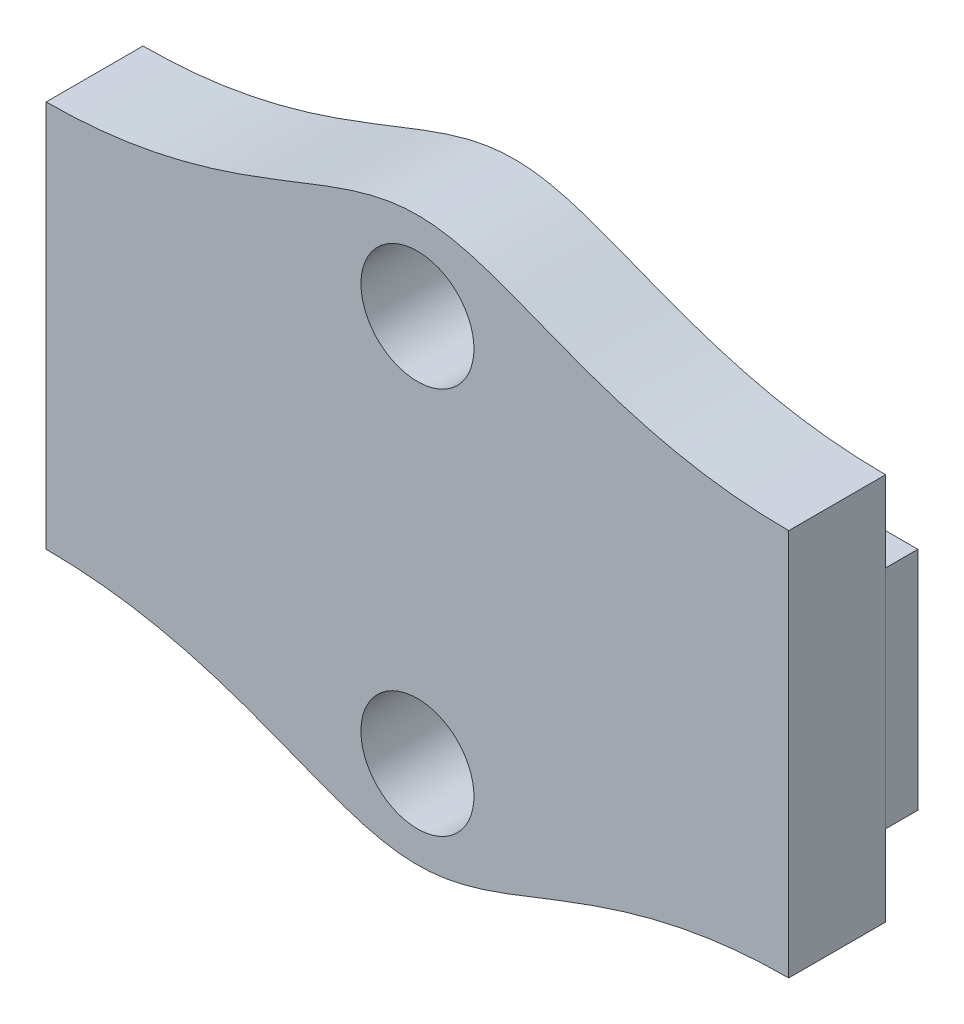
SolidWorks part; units mm, degrees
ref_plane "Plan de face" through (0, 0, 0) normal (0, 0, 1) x (1, 0, 0)
ref_plane "Plan de dessus" through (0, 0, 0) normal (0, 1, 0) x (1, 0, 0)
ref_plane "Plan de droite" through (0, 0, 0) normal (1, 0, 0) x (0, 0, -1)
sketch "Esquisse2" plane through (0, 0, 0) normal (0, 1, 0) x (1, 0, 0)
  line L3 (23, 3) -> (23, 4)
  line L4 (23, 4) -> (22, 4)
  line L5 (22, 4) -> (22, 3)
  line L6 (22, 3) -> (21, 3) construction
  line L7 (21, 3) -> (21, 4)
  line L8 (21, 4) -> (20, 4)
  line L9 (20, 4) -> (20, 3)
  line L10 (20, 3) -> (19, 3) construction
  line L11 (19, 3) -> (19, 4)
  line L12 (19, 4) -> (18, 4)
  line L13 (18, 4) -> (18, 3)
  line L14 (18, 3) -> (17, 3) construction
  line L15 (17, 3) -> (17, 4)
  line L16 (17, 4) -> (16, 4)
  line L17 (16, 4) -> (16, 3)
  line L18 (16, 3) -> (15, 3) construction
  line L19 (15, 3) -> (15, 4)
  line L20 (15, 4) -> (14, 4)
  line L21 (14, 4) -> (14, 3)
  line L22 (14, 3) -> (13, 3) construction
  line L23 (13, 3) -> (13, 4)
  line L24 (13, 4) -> (12, 4)
  line L25 (12, 4) -> (12, 3)
  line L26 (12, 3) -> (11, 3) construction
  line L27 (11, 3) -> (11, 4)
  line L28 (11, 4) -> (10, 4)
  line L29 (10, 4) -> (10, 3)
  line L30 (10, 3) -> (9, 3) construction
  line L31 (9, 3) -> (9, 4)
  line L32 (9, 4) -> (8, 4)
  line L33 (8, 4) -> (8, 3)
  line L34 (8, 3) -> (7, 3) construction
  line L35 (7, 3) -> (7, 4)
  line L36 (7, 4) -> (6, 4)
  line L37 (6, 4) -> (6, 3)
  line L38 (6, 3) -> (5, 3) construction
  line L39 (5, 3) -> (5, 4)
  line L40 (5, 4) -> (4, 4)
  line L41 (4, 4) -> (4, 3)
  line L42 (4, 3) -> (3, 3) construction
  line L43 (3, 3) -> (3, 4)
  line L44 (3, 4) -> (2, 4)
  line L45 (2, 4) -> (2, 3)
  line L46 (2, 3) -> (1, 3) construction
  line L47 (1, 3) -> (1, 4)
  line L48 (1, 4) -> (0, 4)
  line L49 (0, 4) -> (0, 3)
  line L53 (0, 3) -> (-1, 3) [skipped]
  line L56 (0, 3) -> (1, 3)
  line L57 (2, 3) -> (3, 3)
  line L58 (4, 3) -> (5, 3)
  line L59 (6, 3) -> (7, 3)
  line L60 (8, 3) -> (9, 3)
  line L61 (10, 3) -> (11, 3)
  line L62 (12, 3) -> (13, 3)
  line L63 (14, 3) -> (15, 3)
  line L64 (16, 3) -> (17, 3)
  line L65 (18, 3) -> (19, 3)
  line L66 (20, 3) -> (21, 3)
  line L67 (22, 3) -> (23, 3)
  dimension "D1" = 1
  dimension "D2" = 1
  dimension "D3" = 3
  dimension "D4" = 23
  dimension "D5" = 12
extrude "Boss.-Extru.1" add sketch "Esquisse2" along normal blind 7 contours L49 L56 L47 L48 | L41 L58 L39 L40 | L37 L59 L35 L36 | L33 L60 L31 L32 | L29 L61 L27 L28 | L25 L62 L23 L24 | L21 L63 L19 L20 | L17 L64 L15 L16 | L13 L65 L11 L12 | L9 L66 L7 L8 | L5 L67 L3 L4 | L44 L45 L57 L43
sketch "Esquisse3" plane through (0, 7, 0) normal (0, 1, 0) x (1, 0, 0)
  line L1 (0, 0) -> (23, 0)
  line L2 (0, 0) -> (0, 3)
  line L3 (0, 3) -> (23, 3)
  line L4 (23, 0) -> (23, 3)
  dimension "D1" = 3
  dimension "D2" = 23
extrude "Boss.-Extru.2" add sketch "Esquisse3" along direction (0, 1, 0) on the side of the normal blind 6 and the other way offset from surface (13 mm away) 6 separate body
sketch "Esquisse4" plane through (0, 0, -3) normal (0, 0, -1) x (-1, 0, 0)
  line L0 (-11.5, 16.75) -> (-11.5, -6) construction
  line L1 (-23, 13) -> (0, 13) construction
  line L2 (0, -6) -> (-23, -6) construction
  line L3 (-23, 9.5) -> (0, 9.5) construction
  line L4 (-23, -6) -> (-23, 13) construction
  line L5 (0, -6) -> (0, 13) construction
  line L6 (-23, -2.5) -> (0, -2.5) construction
  line L7 (-23, 9.5) -> (-13.25, 9.5) construction
  line L8 (-13.25, 9.5) -> (-11.5, 16.75) construction
  line L9 (-11.5, 16.75) -> (-9.75, 9.5) construction
  line L10 (-9.75, 9.5) -> (0, 9.5) construction
  line L11 (-23, 9.5) -> (-23, 13)
  line L12 (-23, 13) -> (0, 13)
  line L13 (0, 13) -> (0, 9.5)
  line L14 (-11.5, 3.5) -> (0, 3.5) construction
  line L16 (-23, -6) -> (0, -6)
  line L17 (-23, -2.5) -> (-23, -6)
  line L18 (-23, -2.5) -> (-13.25, -2.5) construction
  line L19 (-13.25, -2.5) -> (-11.5, -9.75) construction
  line L20 (-11.5, -9.75) -> (-9.75, -2.5) construction
  line L21 (-9.75, -2.5) -> (0, -2.5) construction
  line L22 (0, -6) -> (0, -2.5)
  circle A0 centre (-11.5, -2.5) radius 1.75
  circle A1 centre (-11.5, 9.5) radius 1.75
  spline S0 degree 4 poles (-23, 9.5) (-13.25, 9.5) (-11.5, 16.75) (-9.75, 9.5) (0, 9.5) knots 0 0 0 0 0 1 1 1 1 1
  spline S1 degree 4 poles (-23, -2.5) (-13.25, -2.5) (-11.5, -9.75) (-9.75, -2.5) (0, -2.5) knots 0 0 0 0 0 1 1 1 1 1
  point P34 (-11.5, 14.3014)
  point P35 (0, 0)
  point P36 (0, 0)
  point P37 (0, 0)
  point P38 (-41.8693, 4.9449)
  dimension "D3" = 3.5
  dimension "D1" = 3.5
  dimension "D2" = 3.5
extrude "Enlèv. mat.-Extru.1" cut sketch "Esquisse4" against normal up to next (3 mm away)
equation "\"D2@Esquisse4\"=\"D1@Esquisse4\""
